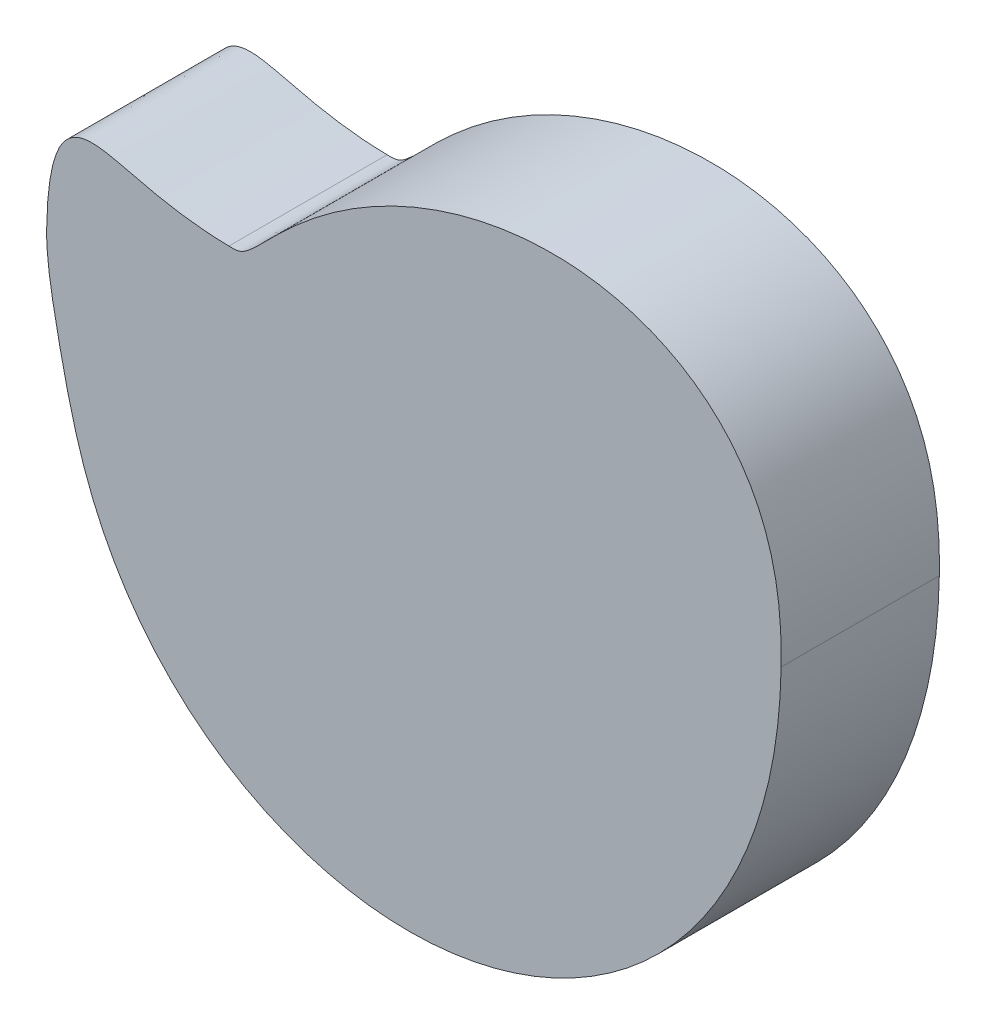
SolidWorks part; units mm, degrees
ref_plane "前视基准面" through (0, 0, 0) normal (0, 0, 1) x (1, 0, 0)
ref_plane "上视基准面" through (0, 0, 0) normal (0, 1, 0) x (1, 0, 0)
ref_plane "右视基准面" through (0, 0, 0) normal (1, 0, 0) x (0, 0, -1)
sketch "草图1" plane through (0, 0, 0) normal (0, 0, 1) x (1, 0, 0)
  spline S0 degree 4 poles (-1.3339, 10.051) (-1.2944, 10.091) (-1.2118, 10.167) (-1.0802, 10.2666) (-0.8897, 10.371) (-0.6935, 10.4445) (-0.4988, 10.492) (-0.3015, 10.5192) (-0.1167, 10.5315) (0.1312, 10.5331) (0.315, 10.5277) (0.6435, 10.519) (0.9137, 10.5261) (1.2, 10.5592) (1.4358, 10.6176) (1.6524, 10.6916) (1.8347, 10.7727) (2.0521, 10.8863) (2.2957, 11.0389) (2.5645, 11.2334) (2.8549, 11.4696) (3.1367, 11.7165) (3.4118, 11.9706) (3.6825, 12.2295) (3.95, 12.4915) (4.2206, 12.7606) (4.495, 13.0359) (4.8448, 13.3885) (5.2703, 13.8177) (5.7684, 14.3169) (6.3421, 14.883) (6.9212, 15.4434) (7.6532, 16.1356) (8.5453, 16.9516) (9.6072, 17.8799) (10.8505, 18.9061) (12.123, 19.8957) (13.7495, 21.0853) (15.4221, 22.2099) (17.4816, 23.478) (19.6023, 24.6409) (21.7687, 25.7164) (24.3577, 26.8388) (27.0029, 27.8237) (30.0932, 28.7498) (33.2393, 29.4644) (37.2259, 30.0759) (42.0658, 30.3282) (46.9088, 29.9147) (51.6201, 28.738) (55.029, 27.3412) (57.2547, 26.1584) (59.3677, 24.7875) (61.0572, 23.4616) (62.6032, 21.9986) (63.9927, 20.4146) (65.0388, 19.0318) (66.0319, 17.5014) (66.9499, 15.8209) (67.734, 14.0732) (68.386, 12.2735) (68.8932, 10.5207) (69.2792, 8.8325) (69.5382, 7.3354) (69.7087, 6.0516) (69.8188, 4.967) (69.8891, 4.1176) (69.9418, 3.2266) (69.9798, 2.4066) (70.001, 1.4643) (70.0121, 0.7255) (70.0055, -0.2674) (69.9971, -0.8083) (69.9788, -1.5657) (69.96, -2.1261) (69.9304, -2.8799) (69.8879, -3.7602) (69.8288, -4.8007) (69.7516, -5.9806) (69.6674, -7.165) (69.5792, -8.3458) (69.5118, -9.2334) (69.4672, -9.8238) (69.4451, -10.1196) knots 0 0 0 0 0 0.002118 0.004235 0.006205 0.008176 0.009994 0.011812 0.013631 0.015449 0.018261 0.021072 0.023883 0.026694 0.028591 0.030487 0.032384 0.03428 0.037814 0.041349 0.044883 0.048417 0.051952 0.055486 0.059021 0.062555 0.066358 0.070161 0.077767 0.085373 0.092979 0.100585 0.108191 0.123403 0.138615 0.153827 0.169039 0.184251 0.214675 0.229887 0.260311 0.275523 0.305947 0.336371 0.366795 0.397219 0.427643 0.488492 0.54934 0.579764 0.610188 0.627267 0.644347 0.67477 0.691121 0.707471 0.723821 0.740172 0.759932 0.779693 0.796043 0.812394 0.828744 0.845094 0.853269 0.861445 0.86962 0.877795 0.88597 0.894145 0.90232 0.910495 0.916089 0.921683 0.927278 0.932872 0.94406 0.955248 0.966436 0.977624 0.988812 1 1 1 1 1 construction
  spline S1 degree 4 poles (0.1783, 10.5309) (0.2449, 10.5298) (0.3733, 10.5262) (0.6435, 10.519) (0.9137, 10.5261) (1.2, 10.5592) (1.4358, 10.6176) (1.6524, 10.6916) (1.8347, 10.7727) (2.0521, 10.8863) (2.2957, 11.0389) (2.5645, 11.2334) (2.8549, 11.4696) (3.1367, 11.7165) (3.4118, 11.9706) (3.6825, 12.2295) (3.95, 12.4915) (4.2206, 12.7606) (4.495, 13.0359) (4.8448, 13.3885) (5.2703, 13.8177) (5.7684, 14.3169) (6.3421, 14.883) (6.9212, 15.4434) (7.6532, 16.1356) (8.5453, 16.9516) (9.6072, 17.8799) (10.8505, 18.9061) (12.123, 19.8957) (13.7495, 21.0853) (15.4221, 22.2099) (17.4816, 23.478) (19.6023, 24.6409) (21.7687, 25.7164) (24.3577, 26.8388) (27.0029, 27.8237) (30.0932, 28.7498) (33.2393, 29.4644) (37.2259, 30.0759) (42.0658, 30.3282) (46.9088, 29.9147) (51.6201, 28.738) (55.029, 27.3412) (57.2547, 26.1584) (59.3677, 24.7875) (61.0572, 23.4616) (62.6032, 21.9986) (63.9927, 20.4146) (65.0388, 19.0318) (66.0319, 17.5014) (66.9499, 15.8209) (67.734, 14.0732) (68.386, 12.2735) (68.8932, 10.5207) (69.2792, 8.8325) (69.5382, 7.3354) (69.7087, 6.0516) (69.8188, 4.967) (69.8891, 4.1176) (69.9418, 3.2266) (69.9798, 2.4066) (70.001, 1.4643) (70.0121, 0.7255) (70.0067, -0.083) (70.0021, -0.4597) (69.9988, -0.6535) knots 0.015449 0.015449 0.015449 0.015449 0.015449 0.018261 0.021072 0.023883 0.026694 0.028591 0.030487 0.032384 0.03428 0.037814 0.041349 0.044883 0.048417 0.051952 0.055486 0.059021 0.062555 0.066358 0.070161 0.077767 0.085373 0.092979 0.100585 0.108191 0.123403 0.138615 0.153827 0.169039 0.184251 0.214675 0.229887 0.260311 0.275523 0.305947 0.336371 0.366795 0.397219 0.427643 0.488492 0.54934 0.579764 0.610188 0.627267 0.644347 0.67477 0.691121 0.707471 0.723821 0.740172 0.759932 0.779693 0.796043 0.812394 0.828744 0.845094 0.853269 0.861445 0.86962 0.877795 0.88597 0.894145 0.90232 0.910495 0.910495 0.910495 0.910495 0.910495
  spline S2 degree 4 poles (68.6171, 14.9747) (68.7081, 14.4921) (68.8827, 13.5254) (69.1222, 12.0715) (69.3954, 10.1258) (69.5928, 8.4182) (69.7314, 6.9511) (69.8261, 5.7271) (69.8892, 4.7465) (69.9394, 3.766) (69.9766, 2.7835) (69.9976, 1.9259) (70.0072, 1.1868) (70.0096, 0.5755) (70.0083, 0.0934) (70.0016, -0.5244) (69.994, -0.9404) (69.9743, -1.7392) (69.9506, -2.3384) (69.91, -3.2341) (69.8488, -4.2349) (69.7563, -5.4447) (69.6228, -6.7985) (69.4605, -8.1634) (69.2692, -9.5163) (69.0486, -10.8696) (68.7983, -12.2148) (68.518, -13.5559) (68.2075, -14.8892) (67.8665, -16.2156) (67.4947, -17.5334) (67.0919, -18.8424) (66.6581, -20.1411) (66.193, -21.4292) (65.6965, -22.7054) (65.0366, -24.2848) (63.8968, -26.7756) (62.4493, -29.4988) (60.6326, -32.4047) (58.6124, -35.1703) (56.8767, -37.2903) (54.5544, -39.823) (51.5435, -42.6418) (47.7251, -45.575) (42.9929, -48.3813) (37.9373, -50.5983) (32.6159, -52.1765) (27.1072, -53.0699) (21.4996, -53.2442) (15.9169, -52.6866) (10.4549, -51.4037) (5.2081, -49.4162) (0.267, -46.7582) (-3.7151, -43.8871) (-6.8372, -41.0736) (-9.2248, -38.5158) (-10.9995, -36.3512) (-12.7304, -33.9428) (-14.3831, -31.2813) (-15.8439, -28.5094) (-17.1147, -25.6463) (-18.1575, -22.8706) (-19.0127, -20.2062) (-19.7564, -17.509) (-20.4134, -14.7897) (-20.9382, -12.3989) (-21.3676, -10.3454) (-21.7119, -8.6313) (-21.9766, -7.2579) (-22.1971, -6.0368) (-22.3738, -4.968) (-22.51, -4.0528) (-22.6114, -3.2915) (-22.6994, -2.5292) (-22.7716, -1.764) (-22.8193, -1.0955) (-22.8452, -0.5655) (-22.8577, -0.1853) (-22.8632, 0.0531) (-22.8661, 0.2482) (-22.8673, 0.4504) (-22.867, 0.6541) (-22.8653, 0.8551) (-22.8621, 1.0336) (-22.8554, 1.2786) (-22.8452, 1.5458) (-22.8292, 1.8608) (-22.8042, 2.229) (-22.7657, 2.6681) (-22.7087, 3.1638) (-22.638, 3.6595) (-22.5532, 4.1522) (-22.3996, 4.9088) (-22.1371, 5.9193) (-21.8332, 6.7881) (-21.5124, 7.5143) (-21.3373, 7.8702) knots 0 0 0 0 0 0.010911 0.021822 0.032733 0.043643 0.049099 0.054554 0.06001 0.065465 0.07092 0.076376 0.079104 0.081831 0.084559 0.087287 0.091089 0.094892 0.098694 0.102496 0.110101 0.117706 0.125311 0.132916 0.14052 0.148125 0.15573 0.163335 0.17094 0.178544 0.186149 0.193754 0.201359 0.208964 0.216568 0.224173 0.239383 0.269802 0.285012 0.300221 0.315431 0.330641 0.361311 0.39173 0.422149 0.452568 0.48364 0.514712 0.545783 0.576855 0.607927 0.638998 0.67007 0.701141 0.716677 0.732213 0.747749 0.763285 0.782521 0.801758 0.817293 0.832829 0.848365 0.863901 0.879436 0.894972 0.90274 0.910508 0.918276 0.926044 0.930308 0.934571 0.938835 0.943099 0.947363 0.951627 0.953759 0.954825 0.955891 0.956957 0.958023 0.959089 0.960155 0.961543 0.962932 0.964321 0.96571 0.968488 0.971265 0.974043 0.976821 0.979598 0.982376 0.991188 1 1 1 1 1 construction
  spline S3 degree 4 poles (69.9988, -0.6535) (69.9963, -0.8028) (69.9902, -1.0946) (69.9743, -1.7392) (69.9506, -2.3384) (69.91, -3.2341) (69.8488, -4.2349) (69.7563, -5.4447) (69.6228, -6.7985) (69.4605, -8.1634) (69.2692, -9.5163) (69.0486, -10.8696) (68.7983, -12.2148) (68.518, -13.5559) (68.2075, -14.8892) (67.8665, -16.2156) (67.4947, -17.5334) (67.0919, -18.8424) (66.6581, -20.1411) (66.193, -21.4292) (65.6965, -22.7054) (65.0366, -24.2848) (63.8968, -26.7756) (62.4493, -29.4988) (60.6326, -32.4047) (58.6124, -35.1703) (56.8767, -37.2903) (54.5544, -39.823) (51.5435, -42.6418) (47.7251, -45.575) (42.9929, -48.3813) (37.9373, -50.5983) (32.6159, -52.1765) (27.1072, -53.0699) (21.4996, -53.2442) (15.9169, -52.6866) (10.4549, -51.4037) (5.2081, -49.4162) (0.267, -46.7582) (-3.7151, -43.8871) (-6.8372, -41.0736) (-9.2248, -38.5158) (-10.9995, -36.3512) (-12.7304, -33.9428) (-14.3831, -31.2813) (-15.8439, -28.5094) (-17.1147, -25.6463) (-18.1575, -22.8706) (-19.0127, -20.2062) (-19.7564, -17.509) (-20.4134, -14.7897) (-20.9382, -12.3989) (-21.3676, -10.3454) (-21.7119, -8.6313) (-21.9766, -7.2579) (-22.1971, -6.0368) (-22.3738, -4.968) (-22.51, -4.0528) (-22.6114, -3.2915) (-22.6994, -2.5292) (-22.7716, -1.764) (-22.8193, -1.0955) (-22.8452, -0.5655) (-22.8577, -0.1853) (-22.8632, 0.0531) (-22.8661, 0.2482) (-22.8673, 0.4504) (-22.867, 0.6541) (-22.8658, 0.7943) (-22.8647, 0.878) (-22.864, 0.9199) knots 0.087287 0.087287 0.087287 0.087287 0.087287 0.091089 0.094892 0.098694 0.102496 0.110101 0.117706 0.125311 0.132916 0.14052 0.148125 0.15573 0.163335 0.17094 0.178544 0.186149 0.193754 0.201359 0.208964 0.216568 0.224173 0.239383 0.269802 0.285012 0.300221 0.315431 0.330641 0.361311 0.39173 0.422149 0.452568 0.48364 0.514712 0.545783 0.576855 0.607927 0.638998 0.67007 0.701141 0.716677 0.732213 0.747749 0.763285 0.782521 0.801758 0.817293 0.832829 0.848365 0.863901 0.879436 0.894972 0.90274 0.910508 0.918276 0.926044 0.930308 0.934571 0.938835 0.943099 0.947363 0.951627 0.953759 0.954825 0.955891 0.956957 0.958023 0.959089 0.960155 0.960155 0.960155 0.960155 0.960155
  spline S4 degree 3 poles (-22.864, 0.9199) (-22.7228, 9.2508) (-18.6663, 16.4026) (-10.3003, 10.7085) (0.1783, 10.5309) knots 0 0 0 0 0.398074 1 1 1 1
extrude "凸台-拉伸1" add sketch "草图1" along normal blind 20
sketch "草图2" plane through (0, 0, 0) normal (1, 0, 0) x (0, 0, -1)
  line L0 (0, 0) -> (-66.0772, 0)
